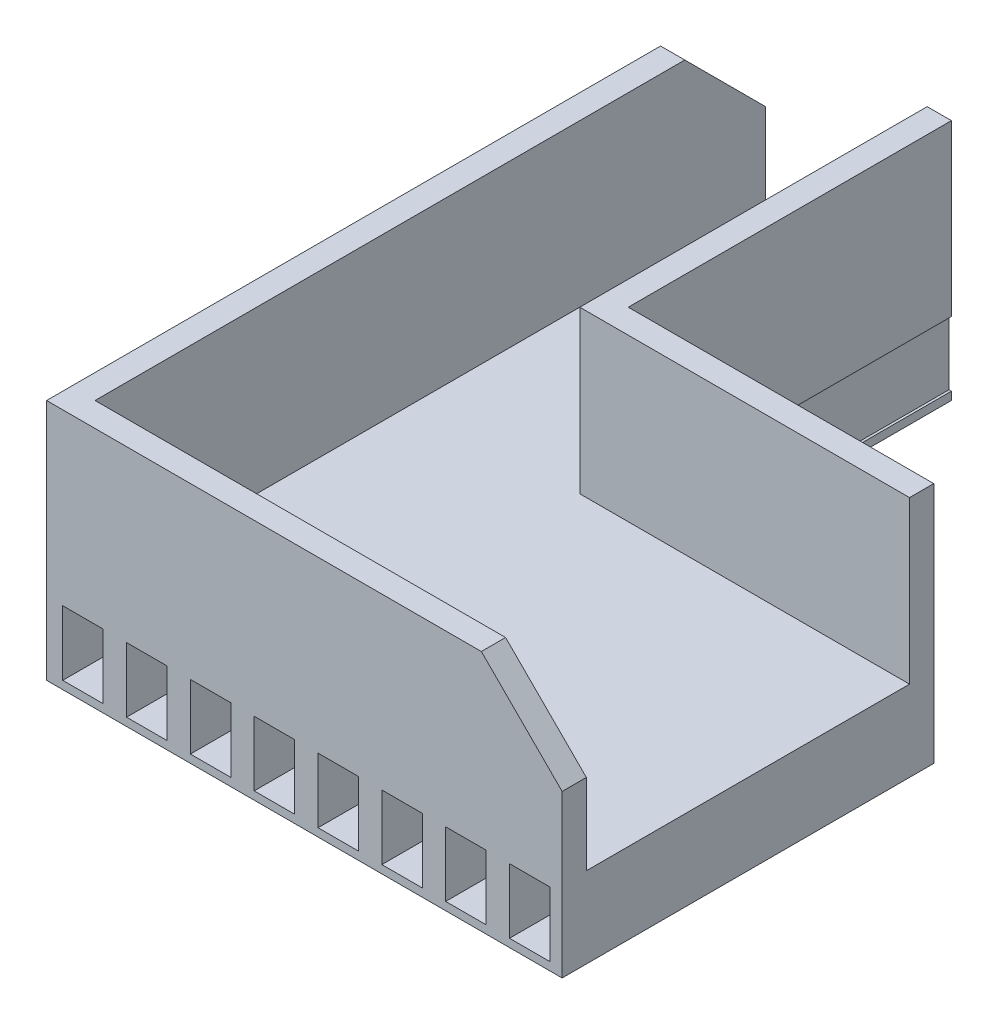
SolidWorks part; units mm, degrees
ref_plane "Front Plane" through (0, 0, 0) normal (0, 0, 1) x (1, 0, 0)
ref_plane "Top Plane" through (0, 0, 0) normal (0, 1, 0) x (1, 0, 0)
ref_plane "Right Plane" through (0, 0, 0) normal (1, 0, 0) x (0, 0, -1)
sketch "Sketch1" plane through (0, 0, 0) normal (0, 1, 0) x (1, 0, 0)
  line L0 (0, 39.0883) -> (0, 0)
  line L1 (0, 0) -> (63.8151, 0)
  line L2 (63.8151, 0) -> (63.8151, 46)
  line L3 (63.8151, 46) -> (26, 46)
  line L4 (26, 46) -> (26, 86)
  line L5 (26, 86) -> (0, 86)
  line L6 (0, 86) -> (0, 39.0883)
  dimension "D1" = 46
  dimension "D2" = 26
  dimension "D3" = 40
extrude "Boss-Extrude1" add sketch "Sketch1" along normal blind 10
sketch "Sketch2" plane through (0, 10, 0) normal (0, 1, 0) x (1, 0, 0)
  line L6 (0, 86) -> (0, 0)
  line L7 (0, 0) -> (63.8151, 0)
  line L8 (63.8151, 0) -> (63.8151, 46)
  line L9 (63.8151, 46) -> (26, 46)
  line L10 (26, 46) -> (26, 86)
  line L11 (26, 86) -> (0, 86)
  line L12 (0, 86) -> (0, 0)
  line L13 (0, 0) -> (63.8151, 0)
  line L15 (63.8151, 46) -> (26, 46)
  line L16 (26, 46) -> (26, 86)
  dimension "D1" = 0
extrude "Extrude-Thin1" add sketch "Sketch2" along normal blind 20 thin thin type one direction reverse wall 3
sketch "Sketch3" plane through (0, 0, 0) normal (-1, 0, 0) x (0, 0, 1)
  line L0 (-86, 5.6686) -> (0, 5.6686) construction
  line L1 (-86, 30) -> (-86, 0) construction
  line L2 (0, 30) -> (0, 0) construction
chamfer "Chamfer1" distance 10 angle 45 2 edges at (1.5, 30, -86) (63.8151, 30, -1.5)
sketch "Sketch4" plane through (0, 0, 0) normal (0, 0, 1) x (1, 0, 0)
  line L0 (63.8151, 5) -> (0, 5) construction
  line L1 (63.8151, 20) -> (63.8151, 0) construction
  line L2 (0, 30) -> (0, 0) construction
  line L3 (0, 0) -> (63.8151, 0) construction
  line L4 (9.9, 9) -> (14.9, 9)
  line L5 (2, 9) -> (7, 9)
  line L6 (2, 9) -> (2, 1)
  line L7 (2, 1) -> (7, 1)
  line L8 (7, 9) -> (7, 1)
  line L9 (2, 9) -> (7, 1) construction
  line L10 (2, 1) -> (7, 9) construction
  line L11 (9.9, 9) -> (9.9, 1)
  line L12 (9.9, 1) -> (14.9, 1)
  line L13 (14.9, 9) -> (14.9, 1)
  line L14 (17.8, 9) -> (22.8, 9)
  line L15 (17.8, 9) -> (17.8, 1)
  line L16 (17.8, 1) -> (22.8, 1)
  line L17 (22.8, 9) -> (22.8, 1)
  line L18 (25.7, 9) -> (30.7, 9)
  line L19 (25.7, 9) -> (25.7, 1)
  line L20 (25.7, 1) -> (30.7, 1)
  line L21 (30.7, 9) -> (30.7, 1)
  line L22 (33.6, 9) -> (38.6, 9)
  line L23 (33.6, 9) -> (33.6, 1)
  line L24 (33.6, 1) -> (38.6, 1)
  line L25 (38.6, 9) -> (38.6, 1)
  line L26 (41.5, 9) -> (46.5, 9)
  line L27 (41.5, 9) -> (41.5, 1)
  line L28 (41.5, 1) -> (46.5, 1)
  line L29 (46.5, 9) -> (46.5, 1)
  line L30 (49.4, 9) -> (54.4, 9)
  line L31 (49.4, 9) -> (49.4, 1)
  line L32 (49.4, 1) -> (54.4, 1)
  line L33 (54.4, 9) -> (54.4, 1)
  line L34 (57.3, 9) -> (62.3, 9)
  line L35 (57.3, 9) -> (57.3, 1)
  line L36 (57.3, 1) -> (62.3, 1)
  line L37 (62.3, 9) -> (62.3, 1)
  point P8 (4.5, 5)
  dimension "D1" = 5
  dimension "D2" = 8
  dimension "D3" = 5
  dimension "D4" = 2
  dimension "D5" = 8
extrude "Cut-Extrude1" cut sketch "Sketch4" against normal blind 99
